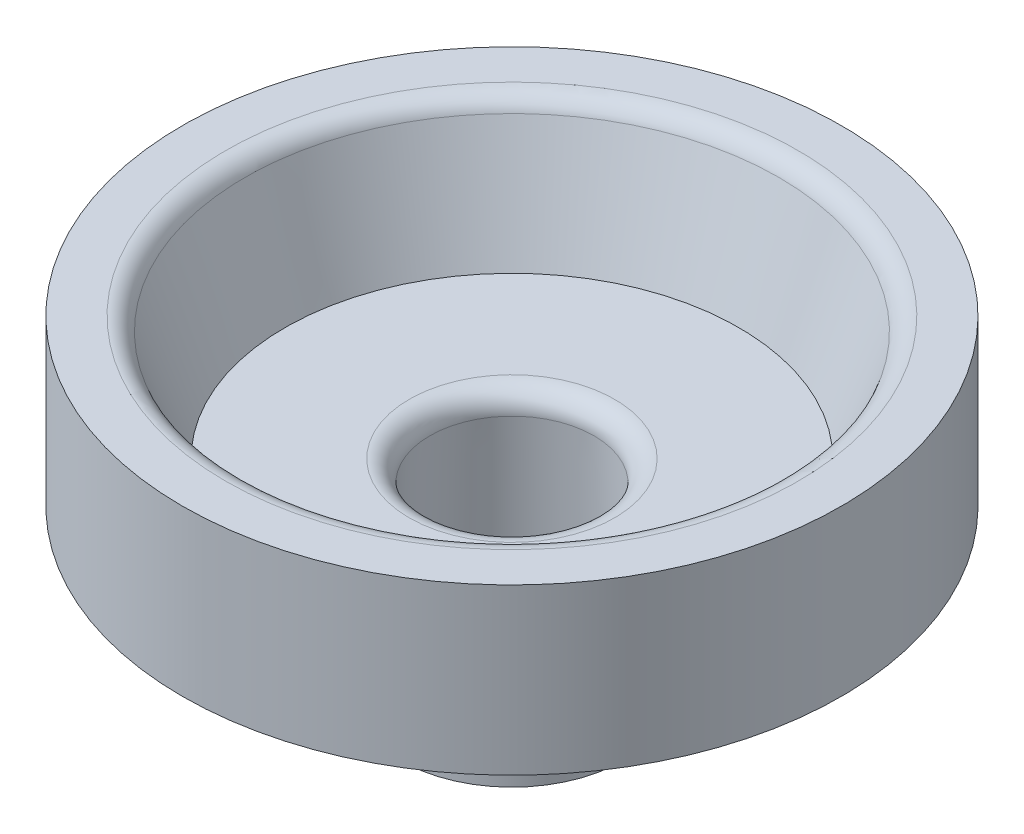
SolidWorks part; units mm, degrees
ref_plane "Front Plane" through (0, 0, 0) normal (0, 0, 1) x (1, 0, 0)
ref_plane "Top Plane" through (0, 0, 0) normal (0, 1, 0) x (1, 0, 0)
ref_plane "Right Plane" through (0, 0, 0) normal (1, 0, 0) x (0, 0, -1)
sketch "Sketch1" plane through (0, 0, 0) normal (0, 1, 0) x (1, 0, 0)
  circle A0 centre (-48.4143, 0) radius 8
  circle A1 centre (-48.4143, 0) radius 7
  circle A2 centre (-48.4143, 0) radius 1.6345
extrude "Boss-Extrude3" add sketch "Sketch1" along normal blind 4 contours A0
sketch "Sketch5" plane through (0, 4, 0) normal (0, 1, 0) x (1, 0, 0)
  circle A0 centre (-48.4143, 0) radius 6.6
  circle A1 centre (-48.4143, 0) radius 8 construction
extrude "Cut-Extrude2" cut sketch "Sketch5" against normal blind 3 draft 20
sketch "Sketch6" plane through (0, 0, 0) normal (0, -1, 0) x (1, 0, 0)
  circle A0 centre (-48.4143, 0) radius 2.7
  circle A1 centre (-48.4143, 0) radius 8 construction
extrude "Boss-Extrude4" add sketch "Sketch6" along normal blind 4
sketch "Sketch7" plane through (0, -4, 0) normal (0, -1, 0) x (1, 0, 0)
  circle A0 centre (-48.4143, 0) radius 2.15
  circle A1 centre (-48.4143, 0) radius 2.7 construction
extrude "Cut-Extrude3" cut sketch "Sketch7" against normal blind 6 draft 2
fillet "Fillet1" radius 0.5 3 edges at (-48.4143, -4, -2.15) (-48.4143, 1, 1.9754) (-48.4143, 4, 6.6)
